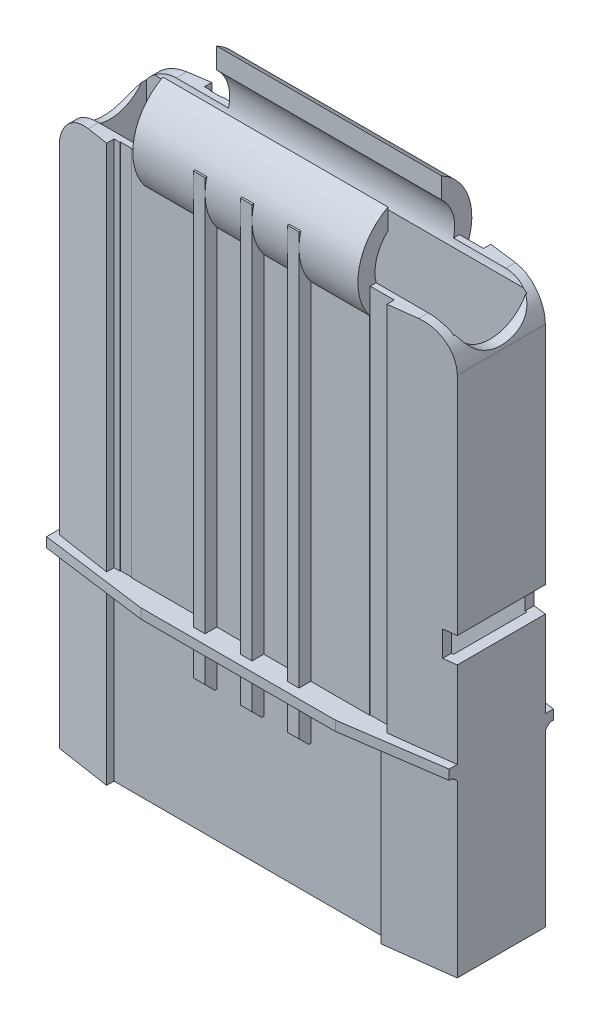
SolidWorks part; units mm, degrees
ref_plane "Front Plane" through (0, 0, 0) normal (0, 0, 1) x (1, 0, 0)
ref_plane "Top Plane" through (0, 0, 0) normal (0, 1, 0) x (1, 0, 0)
ref_plane "Right Plane" through (0, 0, 0) normal (1, 0, 0) x (0, 0, -1)
sketch "Sketch1" plane through (0, 0, 0) normal (0, 1, 0) x (1, 0, 0)
  line L0 (-46.5667, 9) -> (-35.1386, 10.75)
  line L1 (-46.5667, 0) -> (34.7833, 0) construction
  line L2 (-46.5667, 9) -> (-46.5667, -9)
  line L3 (20.9614, -10.75) -> (34.7833, -9)
  line L4 (34.7833, 9) -> (34.7833, -9)
  line L5 (-35.1386, 10.75) -> (-35.1386, 9.25)
  line L6 (-35.1386, 9.25) -> (20.9614, 9.25)
  line L7 (20.9614, 9.25) -> (20.9614, 10.75)
  line L8 (20.9614, 10.75) -> (34.7833, 9)
  line L9 (20.9614, -9.25) -> (20.9614, -10.75)
  line L10 (-35.1386, -9.25) -> (20.9614, -9.25)
  line L11 (-35.1386, -10.75) -> (-35.1386, -9.25)
  line L12 (-46.5667, -9) -> (-35.1386, -10.75)
  dimension "D1" = 9
  dimension "D2" = 9.25
  dimension "D3" = 56.1
  dimension "D4" = 10.75
  dimension "D5" = 10.75
  dimension "D6" = 9
extrude "Boss-Extrude1" add sketch "Sketch1" along normal blind 35.8
sketch "Sketch2" plane through (0, 35.8, 0) normal (0, 1, 0) x (1, 0, 0)
  line L0 (-46.5667, 0) -> (34.7833, 0) construction
  line L1 (-25.3167, 13.6) -> (14.4833, 13.6)
  line L2 (-47.5167, 10.65) -> (-47.5167, -10.65)
  line L3 (14.4833, -13.6) -> (34.7833, -10.65)
  line L4 (34.7833, 10.65) -> (34.7833, -10.65)
  line L5 (-46.5667, 9) -> (-46.5667, -9) construction
  line L6 (34.7833, -9) -> (34.7833, 9) construction
  line L7 (-25.3167, 13.6) -> (-47.5167, 10.65)
  line L8 (14.4833, 13.6) -> (34.7833, 10.65)
  line L9 (-25.3167, -13.6) -> (14.4833, -13.6)
  line L10 (-25.3167, -13.6) -> (-47.5167, -10.65)
  dimension "D2" = 13.6
  dimension "D3" = 82.3
  dimension "D4" = 20.3
  dimension "D5" = 22.2
  dimension "D6" = 10.65
  dimension "D7" = 10.65
extrude "Boss-Extrude2" add sketch "Sketch2" along normal blind 2
sketch "Sketch3" plane through (0, 37.8, 0) normal (0, 1, 0) x (1, 0, 0)
  line L0 (20.9614, 9.25) -> (-35.1386, 9.25) construction
  line L1 (-35.1386, 9.25) -> (-35.1386, 10.75) construction
  line L2 (-35.1386, 10.75) -> (-46.5667, 9) construction
  line L3 (-46.5667, 9) -> (-46.5667, -9) construction
  line L4 (-46.5667, -9) -> (-35.1386, -10.75) construction
  line L5 (-35.1386, -10.75) -> (-35.1386, -9.25) construction
  line L6 (-35.1386, -9.25) -> (20.9614, -9.25) construction
  line L7 (20.9614, -9.25) -> (20.9614, -10.75) construction
  line L8 (20.9614, -10.75) -> (34.7833, -9) construction
  line L9 (34.7833, -10.65) -> (34.7833, 10.65) construction
  line L10 (34.7833, 9) -> (20.9614, 10.75) construction
  line L11 (20.9614, 10.75) -> (20.9614, 9.25) construction
  line L12 (20.9614, 9.25) -> (5.0833, 9.25)
  line L13 (-35.1386, 9.25) -> (-35.1386, 10.75)
  line L14 (-35.1386, 10.75) -> (-46.5667, 9)
  line L15 (-46.5667, 9) -> (-46.5667, -9)
  line L16 (-46.5667, -9) -> (-35.1386, -10.75)
  line L17 (-35.1386, -10.75) -> (-35.1386, -9.25)
  line L18 (-35.1386, -9.25) -> (-16.5167, -9.25)
  line L19 (20.9614, -9.25) -> (20.9614, -10.75)
  line L20 (20.9614, -10.75) -> (34.7833, -9)
  line L21 (34.7833, -9) -> (34.7833, 9)
  line L22 (34.7833, 9) -> (20.9614, 10.75)
  line L23 (20.9614, 10.75) -> (20.9614, 9.25)
  line L24 (-46.5667, 0) -> (34.7833, 0) construction
  line L25 (5.0833, 9.25) -> (5.0833, 11.65)
  line L26 (-16.5167, -9.25) -> (-16.5167, -11.65)
  line L27 (-16.5167, -11.65) -> (-14.1167, -11.65)
  line L28 (-14.1167, -9.25) -> (-14.1167, -11.65)
  line L29 (5.0833, -9.25) -> (20.9614, -9.25)
  line L30 (-6.9167, -9.25) -> (-6.9167, -11.65)
  line L31 (-6.9167, -11.65) -> (-4.5167, -11.65)
  line L32 (-4.5167, -9.25) -> (-4.5167, -11.65)
  line L33 (-4.5167, -9.25) -> (2.6833, -9.25)
  line L34 (2.6833, -9.25) -> (2.6833, -11.65)
  line L35 (2.6833, -11.65) -> (5.0833, -11.65)
  line L36 (5.0833, -9.25) -> (5.0833, -11.65)
  line L37 (-14.1167, -9.25) -> (-6.9167, -9.25)
  line L38 (2.6833, 11.65) -> (5.0833, 11.65)
  line L39 (2.6833, 9.25) -> (2.6833, 11.65)
  line L40 (-4.5167, 9.25) -> (-4.5167, 11.65)
  line L41 (-6.9167, 11.65) -> (-4.5167, 11.65)
  line L42 (-6.9167, 9.25) -> (-6.9167, 11.65)
  line L43 (-14.1167, 9.25) -> (-14.1167, 11.65)
  line L44 (-16.5167, 11.65) -> (-14.1167, 11.65)
  line L45 (-16.5167, 9.25) -> (-16.5167, 11.65)
  line L46 (-16.5167, 9.25) -> (-35.1386, 9.25)
  line L47 (-6.9167, 9.25) -> (-14.1167, 9.25)
  line L48 (2.6833, 9.25) -> (-4.5167, 9.25)
  dimension "D1" = 2.4
  dimension "D2" = 2.4
  dimension "D3" = 2.4
  dimension "D4" = 11.65
  dimension "D5" = 21.6
  dimension "D6" = 7.2
  dimension "D7" = 32.1
extrude "Boss-Extrude3" add sketch "Sketch3" along normal blind 80.75
sketch "Sketch5" plane through (34.7833, 0, 0) normal (1, 0, 0) x (0, 0, -1)
  line L0 (0, 0) -> (0, 170.7554) construction
  line L1 (-9, 118.55) -> (-9, 37.8) construction
  line L2 (-5.5, 125.9) -> (5.5, 125.9)
  line L3 (-9, 0) -> (9, 0) construction
  arc A0 (-5.5, 125.9) -> (5.5, 125.9) centre (0, 115.63) ccw
  dimension "D1" = 23.3
  dimension "D2" = 11
  dimension "D3" = 125.9
extrude "Boss-Extrude4" add sketch "Sketch5" against normal up to surface (81.35 mm away) contours A0 L2 up to face at (-46.5667, 78.175, 0)
sketch "Sketch6" plane through (34.7833, 0, 0) normal (1, 0, 0) x (0, 0, -1)
  line L0 (-5.5, 125.9) -> (-5.5, 121.6444)
  line L1 (5.5, 125.9) -> (5.5, 121.6444)
  line L2 (-5.5, 125.9) -> (5.5, 125.9)
  arc A0 (-5.5, 121.6444) -> (5.5, 121.6444) centre (0, 115.63) ccw
  arc A1 (-5.5, 125.9) -> (-9, 108.2326) centre (0, 115.63) ccw construction
  dimension "D1" = 3.5
extrude "Cut-Extrude1" cut sketch "Sketch6" against normal up to next
sketch "Sketch7" plane through (0, 0, -11.65) normal (0, 0, -1) x (-1, 0, 0)
  line L0 (-34.7833, 0) -> (-20.9614, 0) construction
  line L1 (-34.7833, 125.9) -> (-17.1083, 125.9)
  line L2 (-34.7833, 125.9) -> (-34.7833, 113.7)
  line L3 (-27.7833, 113.7) -> (-17.1083, 113.7)
  line L4 (-17.1083, 125.9) -> (-17.1083, 113.7)
  line L6 (28.8917, 125.9) -> (46.5667, 125.9)
  line L7 (28.8917, 125.9) -> (28.8917, 113.7)
  line L8 (28.8917, 113.7) -> (39.5667, 113.7)
  line L9 (46.5667, 125.9) -> (46.5667, 113.7)
  line L10 (46.5667, 125.9) -> (-34.7833, 125.9) construction
  line L11 (-34.7833, 125.9) -> (-34.7833, 108.2326) construction
  line L12 (46.5667, 108.2326) -> (46.5667, 125.9) construction
  line L13 (-34.7833, 108.2326) -> (-34.7833, 37.8) construction
  line L14 (-34.7833, 113.7) -> (-34.7833, 106.7)
  line L16 (46.5667, 108.2326) -> (46.5667, 37.8) construction
  line L17 (46.5667, 113.7) -> (46.5667, 106.7)
  arc A0 (-27.7833, 113.7) -> (-34.7833, 106.7) centre (-27.7833, 106.7) ccw
  arc A1 (46.5667, 106.7) -> (39.5667, 113.7) centre (39.5667, 106.7) ccw
  dimension "D1" = 113.7
  dimension "D2" = 46
  dimension "D3" = 17.675
  dimension "D4" = 7
  dimension "D5" = 7
  dimension "D6" = 7
  dimension "D7" = 7
extrude "Cut-Extrude2" cut sketch "Sketch7" against normal up to next
sketch "Sketch8" plane through (0, 113.7, 0) normal (0, 1, 0) x (1, 0, 0)
  line L0 (-47.5167, 10.65) -> (-47.5167, -10.65) construction
  line L1 (-45.2667, 7.5) -> (32.5333, 7.5)
  line L2 (-45.2667, 7.5) -> (-45.2667, -7.5)
  line L3 (-45.2667, -7.5) -> (32.5333, -7.5)
  line L4 (32.5333, 7.5) -> (32.5333, -7.5)
  line L7 (-47.5167, 0) -> (34.7833, 0) construction
  line L8 (34.7833, -9) -> (34.7833, 9) construction
  dimension "D1" = 77.8
  dimension "D2" = 2.25
  dimension "D3" = 15
  dimension "D4" = 7.5
extrude "Cut-Extrude3" cut sketch "Sketch8" against normal offset from surface (110.7 mm away) 3 up to face at (-6.6897, 0, 0)
sketch "Sketch9" plane through (34.7833, 0, 0) normal (1, 0, 0) x (0, 0, -1)
  line L0 (-10.65, 37.8) -> (-9, 37.8) construction
  line L2 (-11, 60.62) -> (11, 60.62)
  line L3 (-11, 60.62) -> (-11, 55.42)
  line L4 (-11, 55.42) -> (11, 55.42)
  line L7 (11, 60.62) -> (11, 55.42)
  line L8 (9, 106.7) -> (9, 37.8) construction
  line L9 (-9, 106.7) -> (-9, 37.8) construction
  dimension "D1" = 22.82
  dimension "D2" = 5.2
  dimension "D3" = 2
  dimension "D4" = 2
extrude "Cut-Extrude4" cut sketch "Sketch9" against normal blind 2.65
sketch "Sketch10" plane through (0, 35.8, 0) normal (0, -1, 0) x (1, 0, 0)
  line L0 (-16.5167, 9.25) -> (-16.5167, 11.65) construction
  line L1 (-16.5167, 11.65) -> (-14.1167, 11.65) construction
  line L2 (-14.1167, 11.65) -> (-14.1167, 9.25) construction
  line L3 (-6.9167, 9.25) -> (-6.9167, 11.65) construction
  line L4 (-6.9167, 11.65) -> (-4.5167, 11.65) construction
  line L5 (-4.5167, 11.65) -> (-4.5167, 9.25) construction
  line L6 (2.6833, 9.25) -> (2.6833, 11.65) construction
  line L7 (2.6833, 11.65) -> (5.0833, 11.65) construction
  line L8 (5.0833, 11.65) -> (5.0833, 9.25) construction
  line L9 (-16.5167, -11.65) -> (-16.5167, -9.25) construction
  line L10 (-14.1167, -11.65) -> (-16.5167, -11.65) construction
  line L11 (-14.1167, -9.25) -> (-14.1167, -11.65) construction
  line L12 (-6.9167, -11.65) -> (-6.9167, -9.25) construction
  line L13 (-4.5167, -11.65) -> (-6.9167, -11.65) construction
  line L14 (-4.5167, -9.25) -> (-4.5167, -11.65) construction
  line L15 (2.6833, -11.65) -> (2.6833, -9.25) construction
  line L16 (5.0833, -11.65) -> (2.6833, -11.65) construction
  line L17 (5.0833, -9.25) -> (5.0833, -11.65) construction
  line L18 (-16.5167, 9.25) -> (-16.5167, 11.65)
  line L19 (-16.5167, 11.65) -> (-14.1167, 11.65)
  line L20 (-14.1167, 11.65) -> (-14.1167, 9.25)
  line L21 (-6.9167, 9.25) -> (-6.9167, 11.65)
  line L22 (-6.9167, 11.65) -> (-4.5167, 11.65)
  line L23 (-4.5167, 11.65) -> (-4.5167, 9.25)
  line L24 (2.6833, 9.25) -> (2.6833, 11.65)
  line L25 (2.6833, 11.65) -> (5.0833, 11.65)
  line L26 (5.0833, 11.65) -> (5.0833, 9.25)
  line L27 (-16.5167, -11.65) -> (-16.5167, -9.25)
  line L28 (-14.1167, -11.65) -> (-16.5167, -11.65)
  line L29 (-14.1167, -9.25) -> (-14.1167, -11.65)
  line L30 (-6.9167, -11.65) -> (-6.9167, -9.25)
  line L31 (-4.5167, -11.65) -> (-6.9167, -11.65)
  line L32 (-4.5167, -9.25) -> (-4.5167, -11.65)
  line L33 (2.6833, -11.65) -> (2.6833, -9.25)
  line L34 (5.0833, -11.65) -> (2.6833, -11.65)
  line L35 (5.0833, -9.25) -> (5.0833, -11.65)
  line L36 (-16.5167, -9.25) -> (-14.1167, -9.25)
  line L37 (-16.5167, 9.25) -> (-14.1167, 9.25)
  line L38 (-6.9167, 9.25) -> (-4.5167, 9.25)
  line L39 (2.6833, 9.25) -> (5.0833, 9.25)
  line L40 (-6.9167, -9.25) -> (-4.5167, -9.25)
  line L41 (2.6833, -9.25) -> (5.0833, -9.25)
extrude "Boss-Extrude5" add sketch "Sketch10" along normal blind 9
chamfer "Chamfer1" distance 2 angle 45 6 edges at (3.8833, 26.8, -11.65) (-5.7167, 26.8, -11.65) (-15.3167, 26.8, -11.65) (3.8833, 26.8, 11.65) (-5.7167, 26.8, 11.65) (-15.3167, 26.8, 11.65)
chamfer "Chamfer2" distance 0.9 angle 45 5 edges at (-40.8527, 35.8, 9.875) (-40.8527, 35.8, -9.875) (-46.5667, 35.8, 0)
sketch "Sketch11" plane through (0, 113.7, 0) normal (0, 1, 0) x (1, 0, 0)
  line L0 (-47.5167, 0) -> (34.7833, 0) construction
  line L1 (17.1083, 11.489) -> (22.0083, 11.489)
  line L2 (17.1083, 11.489) -> (17.1083, 9.125)
  line L3 (17.1083, 9.125) -> (22.0083, 9.125)
  line L4 (22.0083, 11.489) -> (22.0083, 9.125)
  line L5 (-47.5167, 10.65) -> (-47.5167, -10.65) construction
  line L6 (34.7833, -9) -> (34.7833, 9) construction
  line L7 (-39.5667, 11.489) -> (-28.8917, 11.489) construction
  line L8 (-33.9517, 11.489) -> (-31.5517, 11.489)
  line L9 (-33.9517, 11.489) -> (-33.9517, 9.125)
  line L10 (-33.9517, 9.125) -> (-31.5517, 9.125)
  line L11 (-31.5517, 11.489) -> (-31.5517, 9.125)
  line L12 (22.0083, -11.489) -> (22.0083, -9.125)
  line L13 (17.1083, -9.125) -> (22.0083, -9.125)
  line L14 (17.1083, -11.489) -> (17.1083, -9.125)
  line L15 (17.1083, -11.489) -> (22.0083, -11.489)
  line L16 (-31.5517, -11.489) -> (-31.5517, -9.125)
  line L17 (-33.9517, -9.125) -> (-31.5517, -9.125)
  line L18 (-33.9517, -11.489) -> (-33.9517, -9.125)
  line L19 (-33.9517, -11.489) -> (-31.5517, -11.489)
  dimension "D1" = 4.9
  dimension "D2" = 9.125
  dimension "D3" = 2.4
  dimension "D4" = 48.66
extrude "Cut-Extrude5" cut sketch "Sketch11" against normal up to surface (75.9 mm away) up to face at (-6.0139, 37.8, 0)
sketch "Sketch12" plane through (0, 113.7, 0) normal (0, 1, 0) x (1, 0, 0)
  line L0 (-35.1386, 10.75) -> (-46.3894, 9.0272) construction
  line L1 (-35.1386, 9.25) -> (-35.1386, 10.75) construction
  line L3 (-35.1386, 10.75) -> (-46.3894, 9.0272)
  line L4 (-35.1386, 9.25) -> (-35.1386, 10.75)
  line L5 (-46.3894, -9.0272) -> (-35.1386, -10.75) construction
  line L6 (-31.5517, 9.25) -> (-16.5167, 9.25) construction
  line L7 (-35.1386, 9.25) -> (-28.8917, 9.25)
  line L8 (-46.3894, 9.0272) -> (-46.3894, 11.5624)
  line L9 (-46.3894, 11.5624) -> (-28.8917, 11.65)
  line L10 (-28.8917, 11.65) -> (-28.8917, 9.25)
  line L11 (-28.8917, 11.65) -> (-28.8917, 5.5) construction
  line L12 (-35.1386, -10.75) -> (-35.1386, -9.25) construction
  line L14 (-35.1386, -9.25) -> (-16.5167, -9.25) construction
  line L15 (-46.3894, -9.0272) -> (-35.1386, -10.75)
  line L16 (-35.1386, -10.75) -> (-35.1386, -9.25)
  line L18 (-35.1386, -9.25) -> (-28.8917, -9.25)
  line L19 (-46.3894, -9.0272) -> (-46.3894, -12.366)
  line L20 (-46.3894, -12.366) -> (-28.8917, -12.366)
  line L21 (-28.8917, -12.366) -> (-28.8917, -9.25)
  line L22 (-28.8917, -5.5) -> (-28.8917, -11.65) construction
  line L23 (34.6073, 9.0223) -> (22.0083, 10.6174) construction
  line L24 (22.0083, 9.125) -> (22.0083, 11.489) construction
  line L25 (17.1083, 9.125) -> (22.0083, 9.125) construction
  line L26 (17.1083, 5.5) -> (17.1083, 11.65) construction
  line L27 (34.6073, 9.0223) -> (22.0083, 10.6174)
  line L28 (22.0083, 9.125) -> (22.0083, 10.6174)
  line L29 (17.1083, 9.125) -> (22.0083, 9.125)
  line L30 (17.1083, 9.125) -> (17.1083, 11.65)
  line L31 (17.1083, 11.65) -> (17.1083, 15.1409)
  line L32 (17.1083, 15.1409) -> (34.6073, 15.1409)
  line L33 (34.6073, 15.1409) -> (34.6073, 9.0223)
  line L34 (22.0083, -10.6174) -> (34.6073, -9.0223) construction
  line L35 (22.0083, -11.489) -> (22.0083, -9.125) construction
  line L36 (22.0083, -9.125) -> (17.1083, -9.125) construction
  line L37 (17.1083, -11.65) -> (17.1083, -5.5) construction
  line L38 (22.0083, -10.6174) -> (34.6073, -9.0223)
  line L39 (22.0083, -10.6174) -> (22.0083, -9.125)
  line L40 (22.0083, -9.125) -> (17.1083, -9.125)
  line L41 (17.1083, -11.65) -> (17.1083, -9.125)
  line L42 (17.1083, -11.65) -> (34.6073, -11.65)
  line L43 (34.6073, -11.65) -> (34.6073, -9.0223)
extrude "Cut-Extrude8" cut sketch "Sketch12" against normal blind 9
